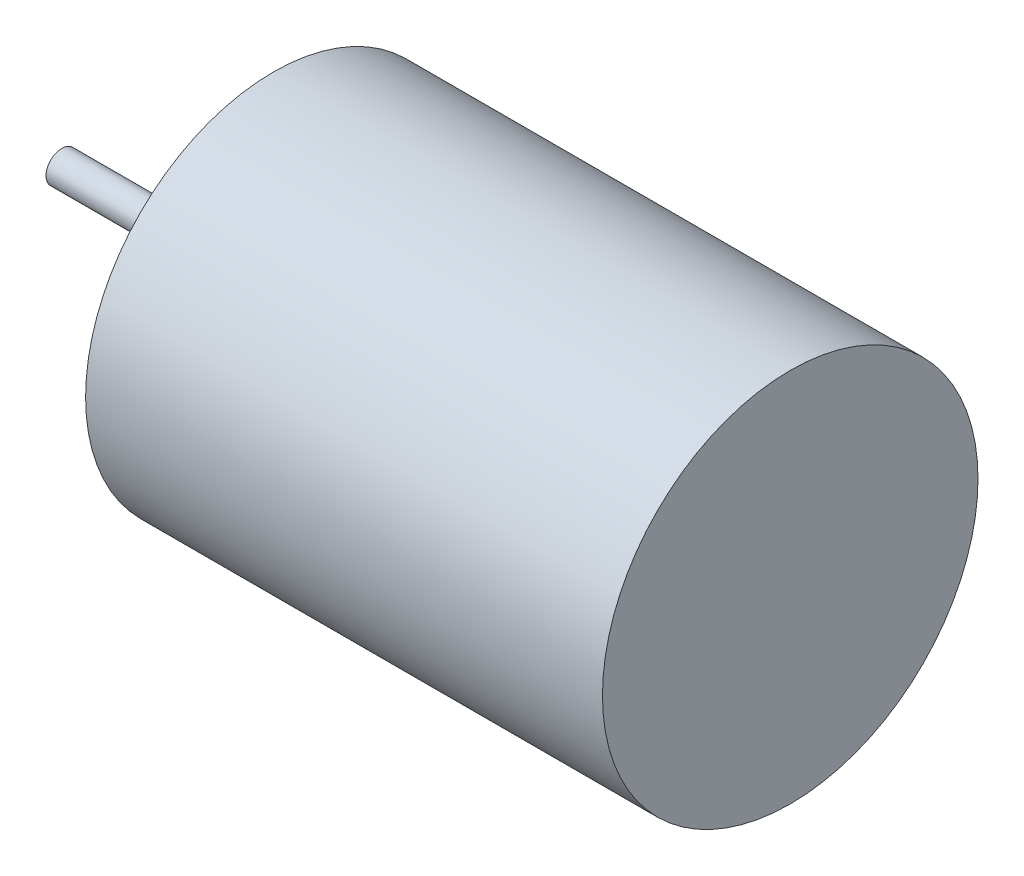
SolidWorks part; units mm, degrees
ref_plane "Front Plane" through (0, 0, 0) normal (0, 0, 1) x (1, 0, 0)
ref_plane "Top Plane" through (0, 0, 0) normal (0, 1, 0) x (1, 0, 0)
ref_plane "Right Plane" through (0, 0, 0) normal (1, 0, 0) x (0, 0, -1)
sketch "Sketch1" plane through (0, 0, 0) normal (0, 0, 1) x (1, 0, 0)
  line L0 (-15.2154, 0) -> (27.7718, 0) construction
  line L1 (0, 0) -> (0, 1.15)
  line L2 (0, 1.15) -> (13, 1.15)
  line L3 (13, 1.15) -> (13, 4.95)
  line L4 (13, 4.95) -> (15.5, 4.95)
  line L5 (15.5, 4.95) -> (15.5, 13.75)
  line L6 (15.5, 13.75) -> (53.35, 13.75)
  line L7 (53.35, 13.75) -> (53.35, 4.7522)
  line L10 (38.9562, 0) -> (0, 0)
  line L11 (53.35, 4.7522) -> (53.35, 0)
  line L12 (53.35, 0) -> (38.9562, 0)
  dimension "D1" = 1.15
  dimension "D2" = 13
  dimension "D3" = 2.5
  dimension "D4" = 37.85
  dimension "D5" = 4.95
  dimension "D6" = 13.75
revolve "Revolve1" add sketch "Sketch1" angle 360 about L0
